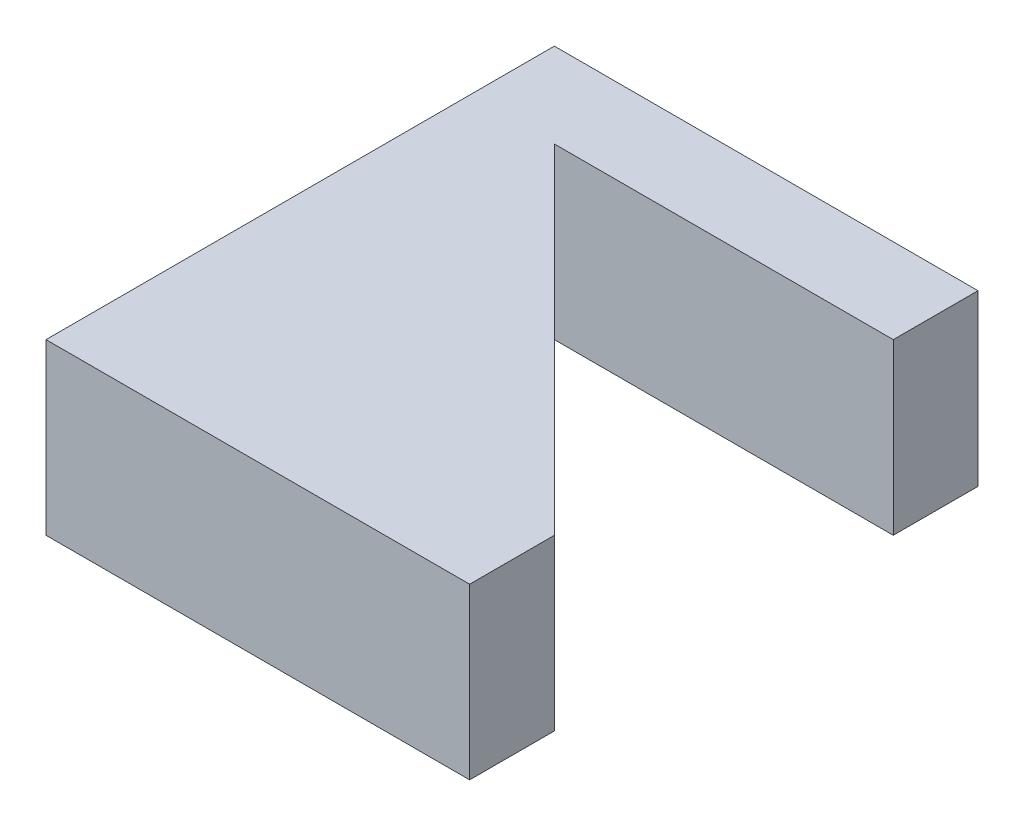
SolidWorks part; units mm, degrees
ref_plane "Přední rovina" through (0, 0, 0) normal (0, 0, 1) x (1, 0, 0)
ref_plane "Horní rovina" through (0, 0, 0) normal (0, 1, 0) x (1, 0, 0)
ref_plane "Pravá rovina" through (0, 0, 0) normal (1, 0, 0) x (0, 0, -1)
sketch "Sketch1" plane through (0, 0, 0) normal (0, 1, 0) x (1, 0, 0)
  line L0 (0, 0) -> (0, -60)
  line L1 (0, -60) -> (50, -60)
  line L2 (50, -60) -> (50, -50)
  line L5 (10, -10) -> (50, -10)
  line L6 (50, -10) -> (50, 0)
  line L7 (50, 0) -> (0, 0)
  line L8 (10, -10) -> (50, -50)
  dimension "D1" = 10
  dimension "D2" = 10
  dimension "D3" = 40
  dimension "D4" = 45
  dimension "D5" = 10
extrude "Boss-Extrude1" add sketch "Sketch1" along normal blind 20 contours L8 L2 L1 L0 L7 L6 L5
equation "\"Angle\"= 45"
equation "\"L\"= 40"
equation "\"D3@Sketch1\"=\"L\""
equation "\"D4@Sketch1\"=\"Angle\""
